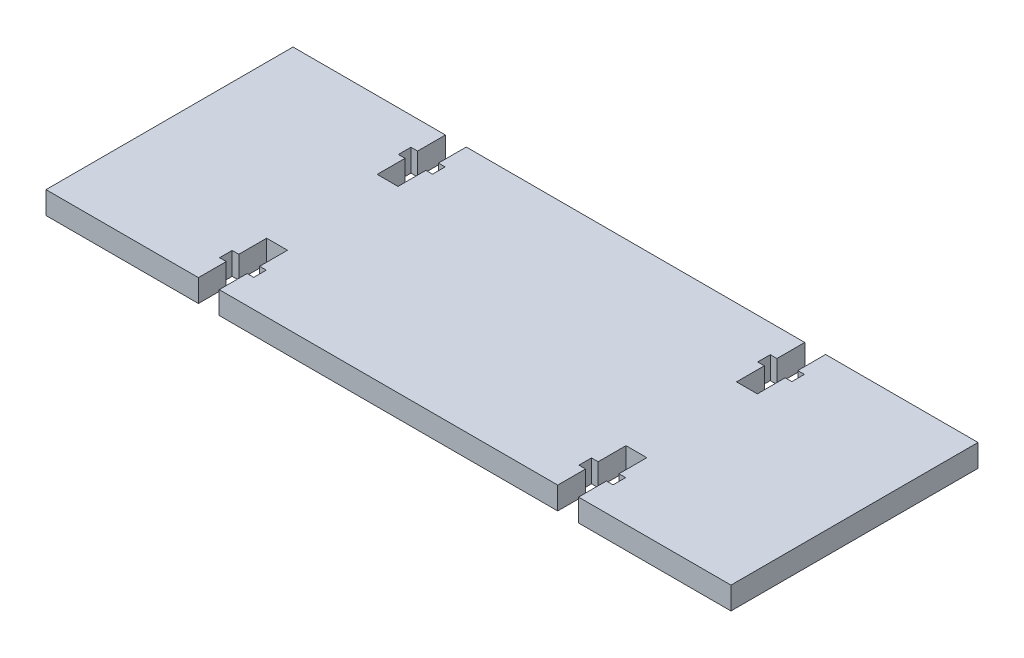
SolidWorks part; units mm, degrees
ref_plane "Front Plane" through (0, 0, 0) normal (0, 0, 1) x (1, 0, 0)
ref_plane "Top Plane" through (0, 0, 0) normal (0, 1, 0) x (1, 0, 0)
ref_plane "Right Plane" through (0, 0, 0) normal (1, 0, 0) x (0, 0, -1)
sketch "Sketch1" plane through (0, 0, 0) normal (0, 1, 0) x (1, 0, 0)
  line L1 (-48.4187, -17.4625) -> (48.4188, -17.4625)
  line L2 (-48.4187, -17.4625) -> (-48.4187, 17.4625)
  line L3 (-48.4187, 17.4625) -> (48.4188, 17.4625)
  line L4 (48.4188, -17.4625) -> (48.4188, 17.4625)
  line L5 (-48.4187, -17.4625) -> (48.4188, 17.4625) construction
  line L6 (-48.4187, 17.4625) -> (48.4188, -17.4625) construction
  point P0 (0, 0)
  dimension "D1" = 96.8375
  dimension "D2" = 34.925
extrude "Boss-Extrude1" add sketch "Sketch1" along normal blind 3.175
sketch "Sketch2" plane through (0, 3.175, 0) normal (0, 1, 0) x (1, 0, 0)
  line L0 (-48.4187, 17.4625) -> (-48.4187, -17.4625) construction
  line L1 (-48.4187, 9.4107) -> (-44.4817, 9.4107)
  line L2 (-48.4187, 9.4107) -> (-48.4187, 6.4643)
  line L3 (-48.4187, 6.4643) -> (-44.4817, 6.4643)
  line L4 (-38.7667, 9.4107) -> (-38.7667, 6.4643)
  line L5 (-48.4187, 9.4107) -> (-38.7667, 6.4643) construction
  line L6 (-48.4187, 7.9375) -> (-38.7667, 7.9375) construction
  line L7 (48.4188, 17.4625) -> (-48.4187, 17.4625) construction
  line L8 (0, 0) -> (0, 17.4625) construction
  line L9 (-44.4817, 5.5245) -> (-42.7037, 5.5245)
  line L10 (-44.4817, 5.5245) -> (-44.4817, 6.4643)
  line L11 (-44.4817, 10.3505) -> (-42.7037, 10.3505)
  line L12 (-42.7037, 5.5245) -> (-42.7037, 6.4643)
  line L13 (-44.4817, 5.5245) -> (-42.7037, 10.3505) construction
  line L14 (-44.4817, 10.3505) -> (-42.7037, 5.5245) construction
  line L15 (-44.4817, 9.4107) -> (-44.4817, 10.3505)
  line L16 (-42.7037, 6.4643) -> (-38.7667, 6.4643)
  line L17 (-42.7037, 9.4107) -> (-42.7037, 10.3505)
  line L18 (-42.7037, 9.4107) -> (-38.7667, 9.4107)
  line L19 (-48.4187, -6.4643) -> (-44.4817, -6.4643)
  line L20 (-48.4187, -6.4643) -> (-48.4187, -9.4107)
  line L21 (-48.4187, -9.4107) -> (-44.4817, -9.4107)
  line L22 (-38.7667, -6.4643) -> (-38.7667, -9.4107)
  line L23 (-44.4817, -10.3505) -> (-42.7037, -10.3505)
  line L24 (-44.4817, -10.3505) -> (-44.4817, -9.4107)
  line L25 (-44.4817, -5.5245) -> (-42.7037, -5.5245)
  line L26 (-42.7037, -10.3505) -> (-42.7037, -9.4107)
  line L27 (-44.4817, -6.4643) -> (-44.4817, -5.5245)
  line L28 (-42.7037, -9.4107) -> (-38.7667, -9.4107)
  line L29 (-42.7037, -6.4643) -> (-42.7037, -5.5245)
  line L30 (-42.7037, -6.4643) -> (-38.7667, -6.4643)
  line L31 (-48.4187, -6.4643) -> (-38.7667, -9.4107) construction
  line L32 (-48.4187, -7.9375) -> (-38.7667, -7.9375) construction
  line L33 (-44.4817, -10.3505) -> (-42.7037, -5.5245) construction
  line L34 (-44.4817, -5.5245) -> (-42.7037, -10.3505) construction
  line L35 (44.4817, -5.5245) -> (42.7037, -10.3505) construction
  line L36 (44.4817, -10.3505) -> (42.7037, -5.5245) construction
  line L37 (48.4187, -7.9375) -> (38.7667, -7.9375) construction
  line L38 (48.4187, -6.4643) -> (38.7667, -9.4107) construction
  line L39 (44.4817, 10.3505) -> (42.7037, 5.5245) construction
  line L40 (44.4817, 5.5245) -> (42.7037, 10.3505) construction
  line L41 (48.4187, 7.9375) -> (38.7667, 7.9375) construction
  line L42 (48.4187, 9.4107) -> (38.7667, 6.4643) construction
  line L43 (42.7037, -6.4643) -> (38.7667, -6.4643)
  line L44 (42.7037, -6.4643) -> (42.7037, -5.5245)
  line L45 (42.7037, -9.4107) -> (38.7667, -9.4107)
  line L46 (44.4817, -6.4643) -> (44.4817, -5.5245)
  line L47 (42.7037, -10.3505) -> (42.7037, -9.4107)
  line L48 (44.4817, -5.5245) -> (42.7037, -5.5245)
  line L49 (44.4817, -10.3505) -> (44.4817, -9.4107)
  line L50 (44.4817, -10.3505) -> (42.7037, -10.3505)
  line L51 (38.7667, -6.4643) -> (38.7667, -9.4107)
  line L52 (48.4187, -9.4107) -> (44.4817, -9.4107)
  line L53 (48.4187, -6.4643) -> (48.4187, -9.4107)
  line L54 (48.4187, -6.4643) -> (44.4817, -6.4643)
  line L55 (42.7037, 9.4107) -> (38.7667, 9.4107)
  line L56 (42.7037, 9.4107) -> (42.7037, 10.3505)
  line L57 (42.7037, 6.4643) -> (38.7667, 6.4643)
  line L58 (44.4817, 9.4107) -> (44.4817, 10.3505)
  line L59 (42.7037, 5.5245) -> (42.7037, 6.4643)
  line L60 (44.4817, 10.3505) -> (42.7037, 10.3505)
  line L61 (44.4817, 5.5245) -> (44.4817, 6.4643)
  line L62 (44.4817, 5.5245) -> (42.7037, 5.5245)
  line L63 (38.7667, 9.4107) -> (38.7667, 6.4643)
  line L64 (48.4187, 6.4643) -> (44.4817, 6.4643)
  line L65 (48.4187, 9.4107) -> (48.4187, 6.4643)
  line L66 (48.4187, 9.4107) -> (44.4817, 9.4107)
  point P10 (-43.5927, 7.9375)
  point P30 (-43.5927, -7.9375)
  point P65 (43.5927, -7.9375)
  point P66 (43.5927, 7.9375)
  dimension "D1" = 9.525
  dimension "D2" = 2.9464
  dimension "D3" = 9.652
  dimension "D4" = 1.778
  dimension "D5" = 4.826
  dimension "D6" = 2
extrude "Cut-Extrude1" [suppressed] cut sketch "Sketch2" against normal through all
sketch "Sketch3" plane through (0, 3.175, 0) normal (0, 1, 0) x (1, 0, 0)
  line L0 (48.4188, 17.4625) -> (-48.4187, 17.4625) construction
  line L1 (-26.8732, 17.4625) -> (-23.9268, 17.4625)
  line L2 (-26.8732, 17.4625) -> (-26.8732, 13.5255)
  line L3 (-26.8732, 7.8105) -> (-23.9268, 7.8105)
  line L4 (-23.9268, 17.4625) -> (-23.9268, 13.5255)
  line L5 (-26.8732, 17.4625) -> (-23.9268, 7.8105) construction
  line L6 (-25.4, 17.4625) -> (-25.4, 7.8105) construction
  line L7 (0, -17.4625) -> (0, 17.4625) construction
  line L8 (-22.987, 13.5255) -> (-23.9268, 13.5255)
  line L9 (-22.987, 13.5255) -> (-22.987, 11.7475)
  line L10 (-22.987, 11.7475) -> (-23.9268, 11.7475)
  line L11 (-27.813, 13.5255) -> (-27.813, 11.7475)
  line L12 (-22.987, 13.5255) -> (-27.813, 11.7475) construction
  line L13 (-22.987, 11.7475) -> (-27.813, 13.5255) construction
  line L14 (0, 0) -> (-48.4188, 0) construction
  line L15 (-48.4187, 17.4625) -> (-48.4187, -17.4625) construction
  line L16 (-26.8732, 13.5255) -> (-27.813, 13.5255)
  line L17 (-26.8732, 11.7475) -> (-26.8732, 7.8105)
  line L18 (-26.8732, 11.7475) -> (-27.813, 11.7475)
  line L19 (-23.9268, 11.7475) -> (-23.9268, 7.8105)
  line L20 (23.9268, 17.4625) -> (26.8732, 17.4625)
  line L21 (23.9268, 17.4625) -> (23.9268, 13.5255)
  line L22 (23.9268, 7.8105) -> (26.8732, 7.8105)
  line L23 (26.8732, 17.4625) -> (26.8732, 13.5255)
  line L24 (27.813, 13.5255) -> (26.8732, 13.5255)
  line L25 (27.813, 13.5255) -> (27.813, 11.7475)
  line L26 (27.813, 11.7475) -> (26.8732, 11.7475)
  line L27 (22.987, 13.5255) -> (22.987, 11.7475)
  line L28 (23.9268, 13.5255) -> (22.987, 13.5255)
  line L29 (23.9268, 11.7475) -> (23.9268, 7.8105)
  line L30 (23.9268, 11.7475) -> (22.987, 11.7475)
  line L31 (26.8732, 11.7475) -> (26.8732, 7.8105)
  line L32 (23.9268, 17.4625) -> (26.8732, 7.8105) construction
  line L33 (25.4, 17.4625) -> (25.4, 7.8105) construction
  line L34 (27.813, 13.5255) -> (22.987, 11.7475) construction
  line L35 (27.813, 11.7475) -> (22.987, 13.5255) construction
  line L36 (27.813, -11.7475) -> (22.987, -13.5255) construction
  line L37 (27.813, -13.5255) -> (22.987, -11.7475) construction
  line L38 (25.4, -17.4625) -> (25.4, -7.8105) construction
  line L39 (23.9268, -17.4625) -> (26.8732, -7.8105) construction
  line L40 (-22.987, -11.7475) -> (-27.813, -13.5255) construction
  line L41 (-22.987, -13.5255) -> (-27.813, -11.7475) construction
  line L42 (-25.4, -17.4625) -> (-25.4, -7.8105) construction
  line L43 (-26.8732, -17.4625) -> (-23.9268, -7.8105) construction
  line L44 (26.8732, -11.7475) -> (26.8732, -7.8105)
  line L45 (23.9268, -11.7475) -> (22.987, -11.7475)
  line L46 (23.9268, -11.7475) -> (23.9268, -7.8105)
  line L47 (23.9268, -13.5255) -> (22.987, -13.5255)
  line L48 (22.987, -13.5255) -> (22.987, -11.7475)
  line L49 (27.813, -11.7475) -> (26.8732, -11.7475)
  line L50 (27.813, -13.5255) -> (27.813, -11.7475)
  line L51 (27.813, -13.5255) -> (26.8732, -13.5255)
  line L52 (26.8732, -17.4625) -> (26.8732, -13.5255)
  line L53 (23.9268, -7.8105) -> (26.8732, -7.8105)
  line L54 (23.9268, -17.4625) -> (23.9268, -13.5255)
  line L55 (23.9268, -17.4625) -> (26.8732, -17.4625)
  line L56 (-23.9268, -11.7475) -> (-23.9268, -7.8105)
  line L57 (-26.8732, -11.7475) -> (-27.813, -11.7475)
  line L58 (-26.8732, -11.7475) -> (-26.8732, -7.8105)
  line L59 (-26.8732, -13.5255) -> (-27.813, -13.5255)
  line L60 (-27.813, -13.5255) -> (-27.813, -11.7475)
  line L61 (-22.987, -11.7475) -> (-23.9268, -11.7475)
  line L62 (-22.987, -13.5255) -> (-22.987, -11.7475)
  line L63 (-22.987, -13.5255) -> (-23.9268, -13.5255)
  line L64 (-23.9268, -17.4625) -> (-23.9268, -13.5255)
  line L65 (-26.8732, -7.8105) -> (-23.9268, -7.8105)
  line L66 (-26.8732, -17.4625) -> (-26.8732, -13.5255)
  line L67 (-26.8732, -17.4625) -> (-23.9268, -17.4625)
  line L68 (48.4188, -17.4625) -> (48.4188, 17.4625) construction
  point P8 (-25.4, 12.6365)
  point P31 (25.4, 12.6365)
  point P67 (25.4, -12.6365)
  point P68 (-25.4, -12.6365)
  dimension "D1" = 9.652
  dimension "D2" = 2.9464
  dimension "D3" = 1.778
  dimension "D4" = 4.826
  dimension "D5" = 25.4
  dimension "D6" = 2
extrude "Cut-Extrude2" cut sketch "Sketch3" against normal through all
